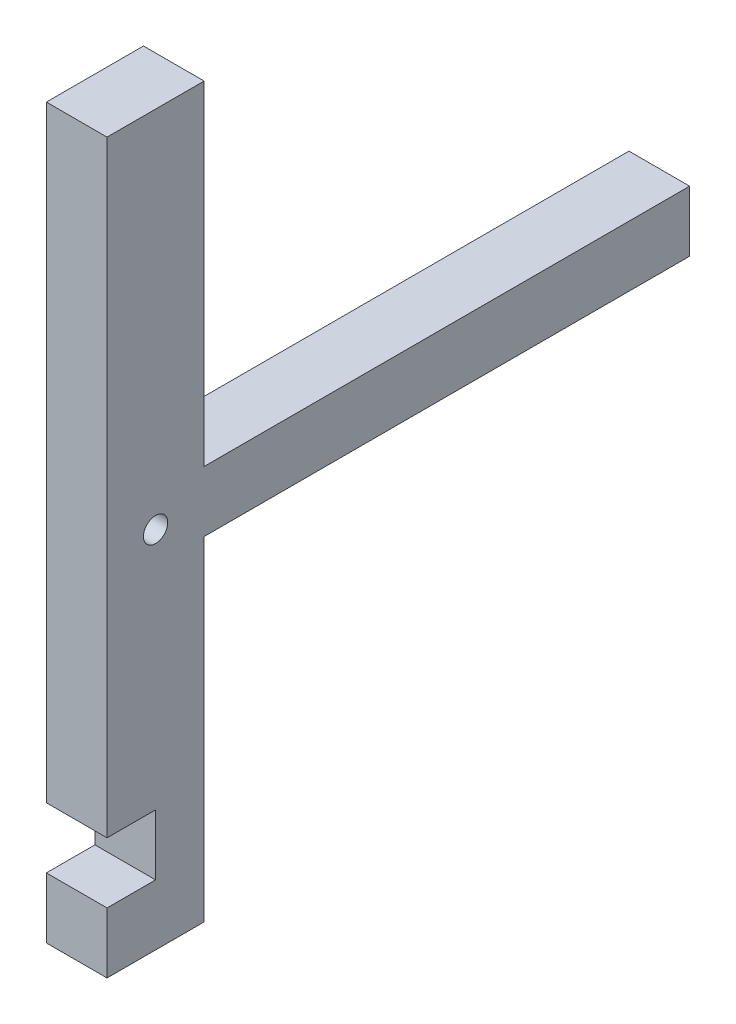
SolidWorks part; units mm, degrees
ref_plane "Front Plane" through (0, 0, 0) normal (0, 0, 1) x (1, 0, 0)
ref_plane "Top Plane" through (0, 0, 0) normal (0, 1, 0) x (1, 0, 0)
ref_plane "Right Plane" through (0, 0, 0) normal (1, 0, 0) x (0, 0, -1)
sketch "Elevator Paddle" plane through (0, 0, 0) normal (1, 0, 0) x (0, 0, -1)
  line L0 (-5.08, 0) -> (55.4696, 0) construction
  line L1 (-5.08, -38.1) -> (5.08, -38.1)
  line L2 (-5.08, -38.1) -> (-5.08, -31.75)
  line L3 (-5.08, 38.1) -> (5.08, 38.1)
  line L4 (5.08, -38.1) -> (5.08, -3.175)
  line L5 (-5.08, -38.1) -> (5.08, 38.1) construction
  line L6 (-5.08, 38.1) -> (5.08, -38.1) construction
  line L7 (5.08, -3.175) -> (55.88, -3.175)
  line L9 (5.08, 3.175) -> (55.88, 3.175)
  line L10 (55.88, -3.175) -> (55.88, 3.175)
  line L11 (0, 38.1) -> (0, -38.1) construction
  line L12 (-5.08, -31.75) -> (0, -31.75)
  line L13 (5.08, 3.175) -> (5.08, 38.1)
  line L14 (-5.08, -25.4) -> (0, -25.4)
  line L15 (0, -31.75) -> (0, -25.4)
  line L16 (-5.08, -25.4) -> (-5.08, 38.1)
  circle A0 centre (0, 0) radius 1.27
  point P0 (0, 0)
  point P14 (55.88, 0)
  dimension "D3" = 2.54
  dimension "D1" = 76.2
  dimension "D2" = 10.16
  dimension "D4" = 6.35
  dimension "D5" = 50.8
  dimension "D6" = 6.35
  dimension "D7" = 6.35
extrude "Boss-Extrude1" add sketch "Elevator Paddle" along normal blind 6.35 contours L16 L14 L15 L12 L2 L1 L4 L7 L10 L9 L13 L3 A0
sketch "Sketch1" plane through (0, 0, 5.08) normal (0, 0, 1) x (1, 0, 0)
  line L0 (3.175, 38.1) -> (3.175, -25.4) construction
  line L1 (6.35, 38.1) -> (0, 38.1) construction
  line L2 (6.35, -25.4) -> (0, -25.4) construction
equation "\"Ball Diameter\"= 1.75in"
equation "\"Sheet Thickness\"= 0.25in"
equation "\"Screw Diameter\"= .17in"
equation "\"Robot Diameter\"= 14in"
equation "\"Castor Screw Diameter\"= 0.22in"
equation "\"Wheel Diameter\" = 4in"
equation "\"Nut Diameter\" = 8.4mm"
equation "\"Nut Height\" = 2.9mm"
equation "\"Screw Height\" = 0.55in"
equation "\"D4@Elevator Paddle\"=\"Sheet Thickness\""
equation "\"D5@Elevator Paddle\"=\"Ball Diameter\"+0.25in"
equation "\"D6@Elevator Paddle\"=\"Sheet Thickness\""
equation "\"D7@Elevator Paddle\"=\"Sheet Thickness\""
equation "\"D1@Boss-Extrude1\"=\"Sheet Thickness\""
